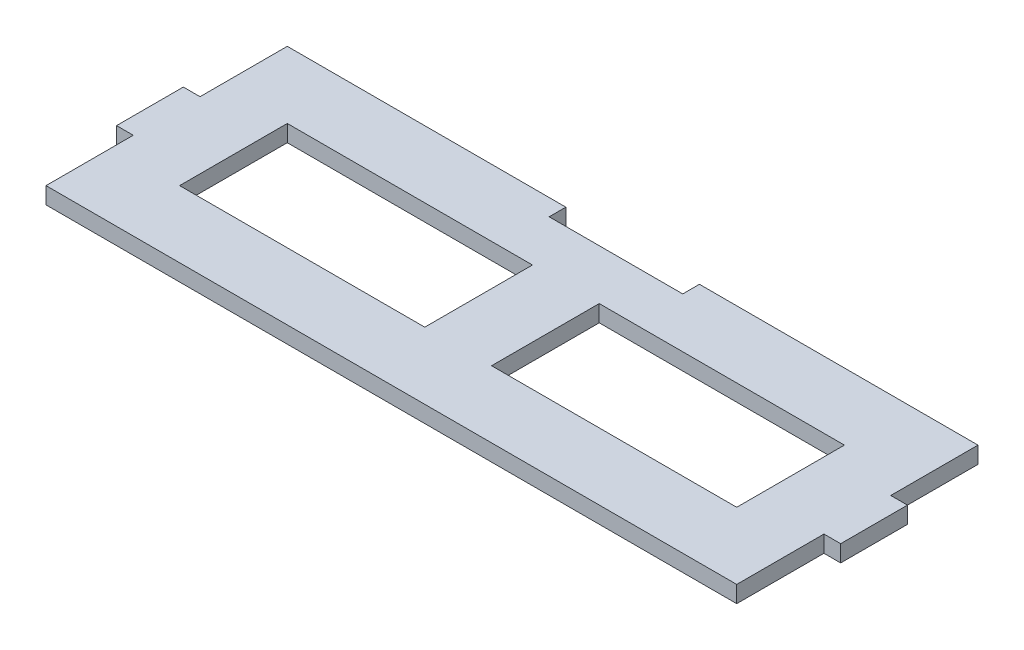
SolidWorks part; units mm, degrees
ref_plane "Front Plane" through (0, 0, 0) normal (0, 0, 1) x (1, 0, 0)
ref_plane "Top Plane" through (0, 0, 0) normal (0, 1, 0) x (1, 0, 0)
ref_plane "Right Plane" through (0, 0, 0) normal (1, 0, 0) x (0, 0, -1)
sketch "Sketch1" plane through (0, 0, 0) normal (0, 1, 0) x (1, 0, 0)
  line L0 (-68.834, 22.9362) -> (-68.834, -22.9362) construction
  line L1 (-65.659, 22.9362) -> (-12.7, 22.9362)
  line L2 (-65.659, 22.9362) -> (-65.659, 6.35)
  line L3 (-65.659, -22.9362) -> (65.659, -22.9362)
  line L4 (65.659, 22.9362) -> (65.659, 6.35)
  line L5 (68.834, 22.9362) -> (68.834, -22.9362) construction
  line L6 (-65.659, 19.7612) -> (65.659, 19.7612) construction
  line L7 (-12.7, 22.9362) -> (-12.7, 19.7612)
  line L8 (-12.7, 19.7612) -> (12.7, 19.7612)
  line L9 (12.7, 19.7612) -> (12.7, 22.9362)
  line L10 (-65.659, 6.35) -> (-68.834, 6.35)
  line L11 (-68.834, 6.35) -> (-68.834, -6.35)
  line L12 (-68.834, -6.35) -> (-65.659, -6.35)
  line L13 (65.659, 6.35) -> (68.834, 6.35)
  line L14 (68.834, 6.35) -> (68.834, -6.35)
  line L15 (68.834, -6.35) -> (65.659, -6.35)
  line L16 (0, 19.7612) -> (0, -22.9362) construction
  line L17 (-52.959, 10.2362) -> (-6.35, 10.2362)
  line L18 (-52.959, 10.2362) -> (-52.959, -10.2362)
  line L19 (-52.959, -10.2362) -> (-6.35, -10.2362)
  line L20 (52.959, 10.2362) -> (52.959, -10.2362)
  line L21 (-6.35, 10.2362) -> (-6.35, -10.2362)
  line L22 (6.35, 10.2362) -> (6.35, -10.2362)
  line L23 (6.35, 10.2362) -> (52.959, 10.2362)
  line L24 (6.35, -10.2362) -> (52.959, -10.2362)
  line L25 (-65.659, -6.35) -> (-65.659, -22.9362)
  line L26 (65.659, -6.35) -> (65.659, -22.9362)
  line L27 (12.7, 22.9362) -> (65.659, 22.9362)
  point P30 (-52.959, 0)
  dimension "D1" = 131.318
  dimension "D2" = 45.8724
  dimension "D3" = 3.175
  dimension "D4" = 3.175
  dimension "D5" = 3.175
  dimension "D6" = 25.4
  dimension "D7" = 52.959
  dimension "D8" = 12.7
  dimension "D9" = 12.7
  dimension "D10" = 16.5862
  dimension "D11" = 16.5862
  dimension "D12" = 12.7
  dimension "D13" = 12.7
  dimension "D14" = 6.35
  dimension "D15" = 6.35
extrude "Boss-Extrude1" add sketch "Sketch1" along normal blind 3.175
